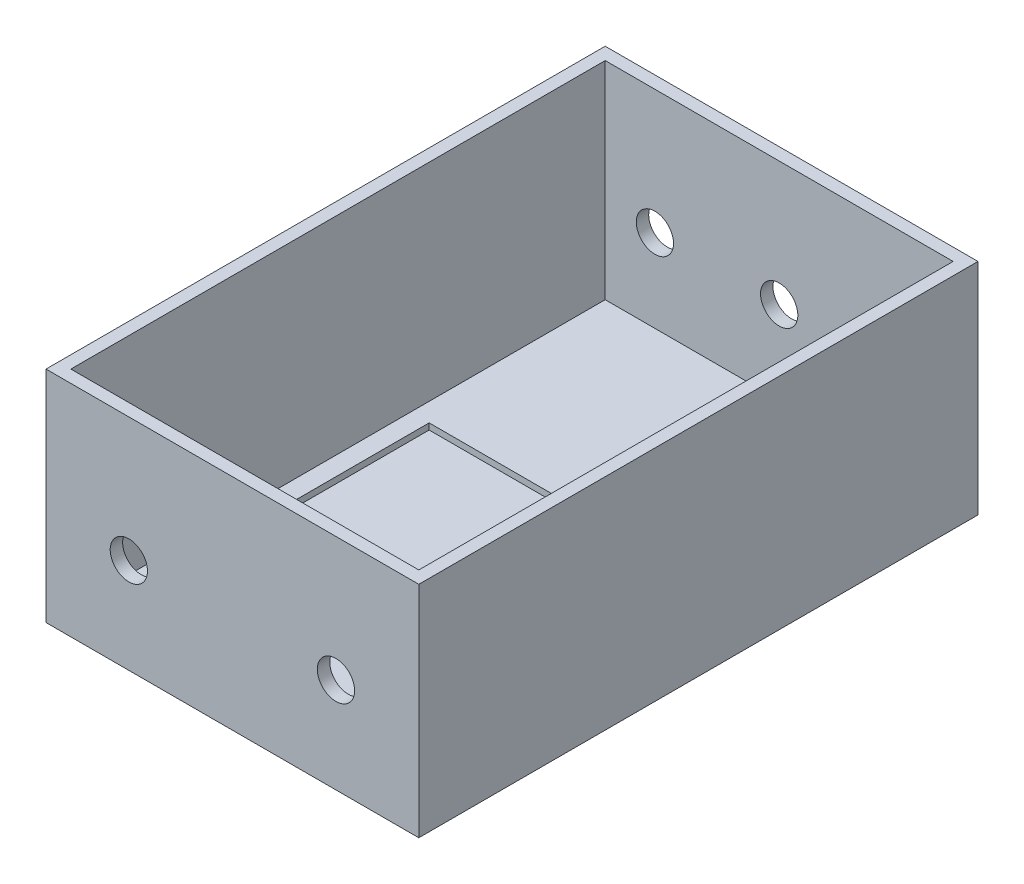
SolidWorks part; units mm, degrees
ref_plane "Front Plane" through (0, 0, 0) normal (0, 0, 1) x (1, 0, 0)
ref_plane "Top Plane" through (0, 0, 0) normal (0, 1, 0) x (1, 0, 0)
ref_plane "Right Plane" through (0, 0, 0) normal (1, 0, 0) x (0, 0, -1)
sketch "Sketch1" plane through (0, 0, 0) normal (0, 1, 0) x (1, 0, 0)
  line L1 (-45, -67.5) -> (45, -67.5)
  line L2 (-45, -67.5) -> (-45, 67.5)
  line L3 (-45, 67.5) -> (45, 67.5)
  line L4 (45, -67.5) -> (45, 67.5)
  line L5 (-45, -67.5) -> (45, 67.5) construction
  line L6 (-45, 67.5) -> (45, -67.5) construction
  point P0 (0, 0)
  dimension "D1" = 135
  dimension "D2" = 90
extrude "Boss-Extrude1" add sketch "Sketch1" along normal blind 3
sketch "Sketch2" plane through (0, 3, 0) normal (0, 1, 0) x (1, 0, 0)
  line L1 (-37.5, -17.5) -> (37.5, -17.5)
  line L2 (-37.5, -17.5) -> (-37.5, 17.5)
  line L3 (-37.5, 17.5) -> (37.5, 17.5)
  line L4 (37.5, -17.5) -> (37.5, 17.5)
  line L5 (-37.5, -17.5) -> (37.5, 17.5) construction
  line L6 (-37.5, 17.5) -> (37.5, -17.5) construction
  point P0 (0, 0)
  dimension "D1" = 35
  dimension "D2" = 75
extrude "Cut-Extrude1" cut sketch "Sketch2" against normal blind 1.5
sketch "Sketch3" plane through (0, 3, 0) normal (0, 1, 0) x (1, 0, 0)
  line L0 (-45, 67.5) -> (-45, -67.5)
  line L1 (-45, -67.5) -> (45, -67.5)
  line L2 (45, -67.5) -> (45, 67.5)
  line L3 (45, 67.5) -> (-45, 67.5)
  line L4 (-45, 67.5) -> (-42, 67.5) construction
  line L5 (-42, 67.5) -> (-42, 64.5) construction
  line L6 (-42, -67.5) -> (-42, -64.5) construction
  line L7 (-42, 64.5) -> (-42, -64.5)
  line L8 (45, -67.5) -> (42, -67.5) construction
  line L9 (42, -67.5) -> (42, -64.5) construction
  line L10 (-42, -64.5) -> (42, -64.5)
  line L11 (42, -64.5) -> (42, 64.5)
  line L12 (42, 64.5) -> (-42, 64.5)
  dimension "D1" = 3
  dimension "D2" = 3
extrude "Boss-Extrude2" add sketch "Sketch3" along normal blind 50
sketch "Sketch4" plane through (0, 0, 67.5) normal (0, 0, 1) x (1, 0, 0)
  line L0 (0, 0) -> (0, 23) construction
  line L1 (0, 23) -> (-25, 23) construction
  line L2 (0, 23) -> (25, 23) construction
  circle A0 centre (-25, 23) radius 4.5
  circle A1 centre (25, 23) radius 4.5
  dimension "D3" = 9
  dimension "D1" = 23
  dimension "D2" = 25
extrude "Cut-Extrude2" cut sketch "Sketch4" against normal blind 3
sketch "Sketch5" plane through (0, 0, -67.5) normal (0, 0, -1) x (-1, 0, 0)
  line L0 (0, 0) -> (0, 23) construction
  line L1 (0, 23) -> (30, 23) construction
  line L2 (0, 23) -> (-30, 23) construction
  circle A0 centre (-30, 23) radius 4.5
  circle A1 centre (0, 23) radius 4.5
  circle A2 centre (30, 23) radius 4.5
  dimension "D3" = 9
  dimension "D1" = 23
  dimension "D2" = 30
extrude "Cut-Extrude3" cut sketch "Sketch5" against normal blind 3
